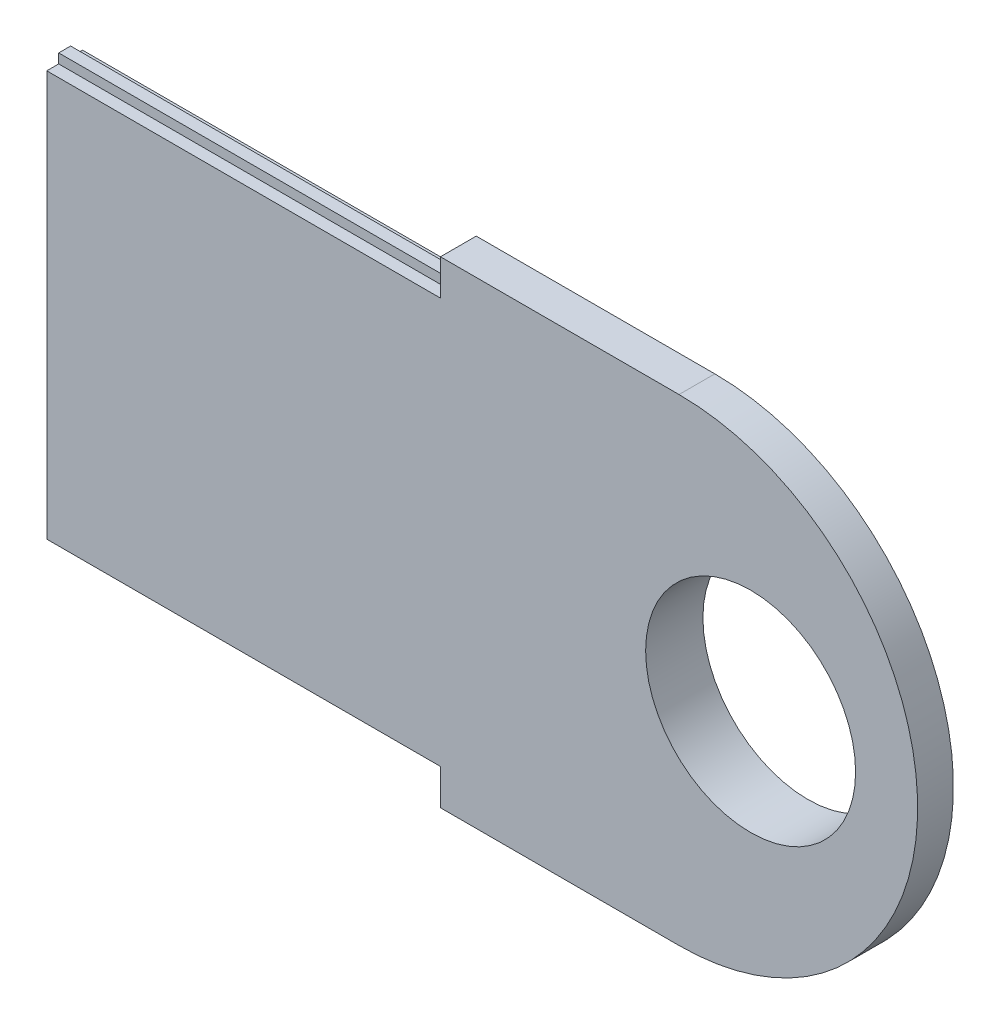
SolidWorks part; units mm, degrees
ref_plane "Front Plane" through (0, 0, 0) normal (0, 0, 1) x (1, 0, 0)
ref_plane "Top Plane" through (0, 0, 0) normal (0, 1, 0) x (1, 0, 0)
ref_plane "Right Plane" through (0, 0, 0) normal (1, 0, 0) x (0, 0, -1)
sketch "Sketch1" plane through (0, 0, 0) normal (0, 0, 1) x (1, 0, 0)
  line L0 (20.955, -25.4) -> (20.955, -21.59)
  line L1 (20.955, -21.59) -> (-20.955, -21.59)
  line L2 (20.955, -21.59) -> (20.955, 21.59) construction
  line L3 (20.955, 21.59) -> (-20.955, 21.59)
  line L4 (-20.955, -21.59) -> (-20.955, 21.59)
  line L5 (20.955, -21.59) -> (-20.955, 21.59) construction
  line L6 (20.955, 21.59) -> (-20.955, -21.59) construction
  line L7 (20.955, 21.59) -> (46.355, 21.59) construction
  line L8 (20.955, 21.59) -> (20.955, -21.59) construction
  line L9 (20.955, -21.59) -> (46.355, -21.59) construction
  line L10 (46.355, 21.59) -> (46.355, -21.59) construction
  line L11 (46.355, -25.4) -> (20.955, -25.4)
  line L12 (46.355, -25.4) -> (46.355, 25.4) construction
  line L13 (46.355, 25.4) -> (20.955, 25.4)
  line L14 (20.955, -25.4) -> (20.955, 25.4) construction
  line L15 (46.355, -25.4) -> (20.955, 25.4) construction
  line L16 (46.355, 25.4) -> (20.955, -25.4) construction
  line L17 (20.955, 25.4) -> (20.955, 21.59)
  circle A1 centre (53.975, 0) radius 11.176
  arc A2 (46.355, 25.4) -> (46.355, -25.4) centre (46.355, 0) cw
  point P0 (0, 0)
  point P11 (33.655, 0)
  dimension "D4" = 22.352
  dimension "D1" = 43.18
  dimension "D2" = 41.91
  dimension "D3" = 25.4
  dimension "D5" = 7.62
  dimension "D6" = 50.8
extrude "Boss-Extrude1" add sketch "Sketch1" along normal blind 3.81
sketch "Sketch2" plane through (0, -21.59, 0) normal (0, -1, 0) x (1, 0, 0)
  line L0 (-20.955, 3.81) -> (-20.955, 0) construction
  line L1 (-20.955, 2.54) -> (20.955, 2.54)
  line L2 (-20.955, 2.54) -> (-20.955, 1.27)
  line L3 (-20.955, 1.27) -> (20.955, 1.27)
  line L4 (20.955, 2.54) -> (20.955, 1.27)
  line L6 (-20.955, 3.81) -> (20.955, 3.81) construction
  dimension "D1" = 1.27
  dimension "D2" = 1.27
extrude "Boss-Extrude2" add sketch "Sketch2" along normal blind 1.016
mirror "Mirror1" about plane through (0, 0, 0) normal (0, 1, 0) of "Boss-Extrude2"
sketch "Sketch3" plane through (-20.955, 0, 0) normal (-1, 0, 0) x (0, 0, 1)
  line L0 (3.81, 21.59) -> (3.81, -21.59) construction
  line L1 (11.43, -3.81) -> (3.81, -3.81)
  line L2 (11.43, -3.81) -> (11.43, 3.81)
  line L3 (11.43, 3.81) -> (3.81, 3.81)
  line L4 (3.81, -3.81) -> (3.81, 3.81)
  line L5 (11.43, -3.81) -> (3.81, 3.81) construction
  line L6 (11.43, 3.81) -> (3.81, -3.81) construction
  circle A0 centre (7.62, 0) radius 1.27
  point P0 (7.62, 0)
  dimension "D2" = 2.54
  dimension "D1" = 7.62
sketch "Sketch4" plane through (0, 0, 0) normal (0, 0, -1) x (-1, 0, 0)
  circle A0 centre (-53.975, 0) radius 11.176
  circle A1 centre (-53.975, 0) radius 11.176 construction
  circle A2 centre (-53.975, 0) radius 13.716
  dimension "D1" = 2.54
extrude "Boss-Extrude4" add sketch "Sketch4" along normal blind 2.286
